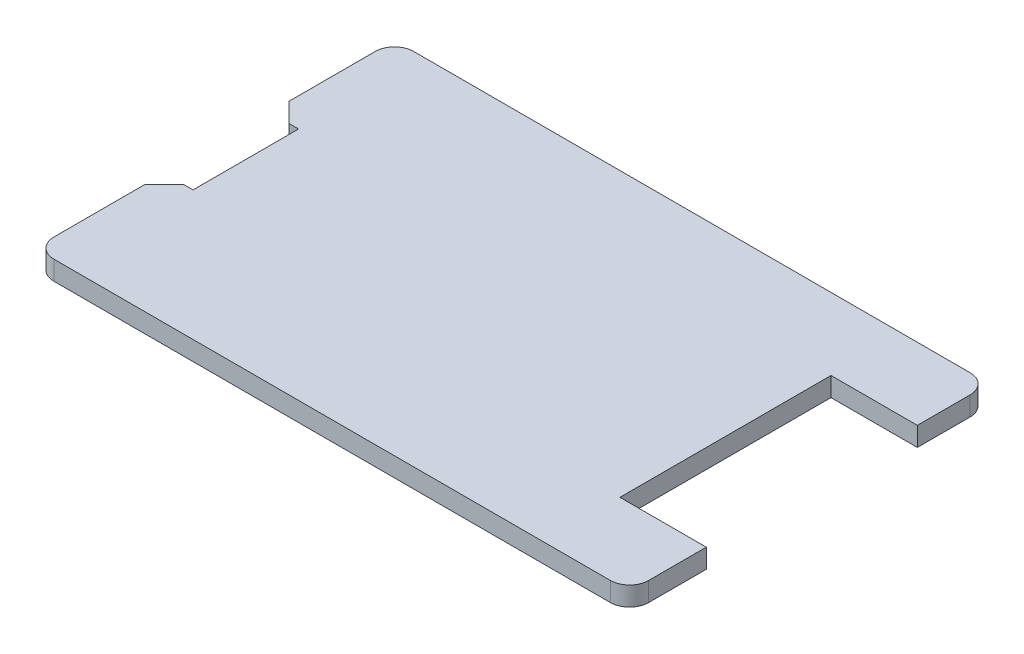
SolidWorks part; units mm, degrees
ref_plane "Front Plane" through (0, 0, 0) normal (0, 0, 1) x (1, 0, 0)
ref_plane "Top Plane" through (0, 0, 0) normal (0, 1, 0) x (1, 0, 0)
ref_plane "Right Plane" through (0, 0, 0) normal (1, 0, 0) x (0, 0, -1)
sketch "Sketch1" plane through (0, 0, 0) normal (0, 1, 0) x (1, 0, 0)
  line L1 (-29.25, -24.8489) -> (28.75, -24.8489)
  line L2 (-31.25, -22.8489) -> (-31.25, 10.6511)
  line L3 (-29.25, 12.6511) -> (28.75, 12.6511)
  line L4 (30.75, -22.8489) -> (30.75, 10.6511)
  line L5 (-31.25, -24.8489) -> (30.75, 12.6511) construction
  line L6 (-31.25, 12.6511) -> (30.75, -24.8489) construction
  arc A0 (-29.25, -24.8489) -> (-31.25, -22.8489) centre (-29.25, -22.8489) cw
  arc A1 (28.75, -24.8489) -> (30.75, -22.8489) centre (28.75, -22.8489) ccw
  arc A2 (28.75, 12.6511) -> (30.75, 10.6511) centre (28.75, 10.6511) cw
  arc A3 (-31.25, 10.6511) -> (-29.25, 12.6511) centre (-29.25, 10.6511) cw
  point P0 (-0.25, -6.0989)
  dimension "D3" = 2
  dimension "D1" = 62
  dimension "D2" = 37.5
sketch "Sketch2" plane through (0, 0, 0) normal (0, 1, 0) x (1, 0, 0)
extrude "Boss-Extrude1" add sketch "Sketch1" along normal blind 2
sketch "Sketch3" plane through (0, 2, 0) normal (0, 1, 0) x (1, 0, 0)
  line L0 (-31.25, 10.6511) -> (-31.25, -22.8489) construction
  line L1 (-31.25, -0.3489) -> (-28.25, -0.3489)
  line L2 (-31.25, -0.3489) -> (-31.25, -11.3489)
  line L3 (-31.25, -11.3489) -> (-28.25, -11.3489)
  line L4 (-28.25, -0.3489) -> (-28.25, -11.3489)
  line L5 (28.75, 12.6511) -> (-29.25, 12.6511) construction
  dimension "D1" = 11
  dimension "D2" = 13
  dimension "D3" = 3
extrude "Cut-Extrude1" cut sketch "Sketch3" against normal blind 2
chamfer "Chamfer1" distance 2 angle 45 2 edges at (-31.25, 1, 11.3489) (-31.25, 1, 0.3489)
sketch "Sketch4" plane through (0, 2, 0) normal (0, 1, 0) x (1, 0, 0)
  line L0 (30.75, -22.8489) -> (30.75, 10.6511) construction
  line L1 (30.75, 5.1511) -> (21.75, 5.1511)
  line L2 (30.75, 5.1511) -> (30.75, -16.8489)
  line L3 (30.75, -16.8489) -> (21.75, -16.8489)
  line L4 (21.75, 5.1511) -> (21.75, -16.8489)
  line L5 (28.75, 12.6511) -> (-29.25, 12.6511) construction
  dimension "D1" = 22
  dimension "D2" = 7.5
  dimension "D3" = 9
extrude "Cut-Extrude2" cut sketch "Sketch4" against normal blind 2
